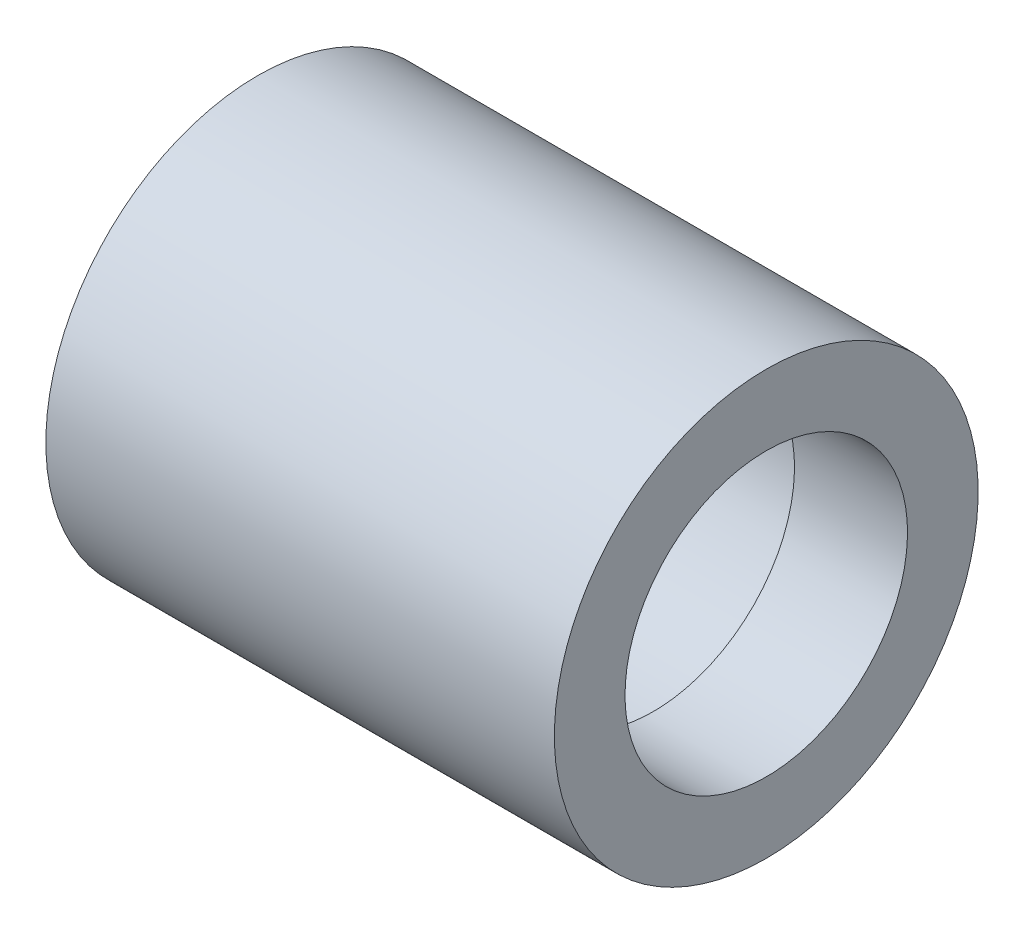
SolidWorks part; units mm, degrees
ref_plane "Front Plane" through (0, 0, 0) normal (0, 0, 1) x (1, 0, 0)
ref_plane "Top Plane" through (0, 0, 0) normal (0, 1, 0) x (1, 0, 0)
ref_plane "Right Plane" through (0, 0, 0) normal (1, 0, 0) x (0, 0, -1)
sketch "Sketch1" plane through (0, 0, 0) normal (0, 0, 1) x (1, 0, 0)
  line L0 (0, 0) -> (0, 26.2355) construction
  line L1 (17, 15) -> (-19, 15)
  line L2 (17, 15) -> (17, 10)
  line L3 (-19, 15) -> (-19, 10)
  line L4 (17, 10) -> (9, 10)
  line L5 (9, 10) -> (9, 12)
  line L6 (9, 12) -> (-9, 12)
  line L7 (-9, 12) -> (-9, 10)
  line L8 (-9, 10) -> (-19, 10)
  line L9 (30.7075, 0) -> (-32.7578, 0) construction
  dimension "D1" = 15
  dimension "D2" = 17
  dimension "D3" = 36
  dimension "D4" = 5
  dimension "D5" = 8
  dimension "D6" = 2
  dimension "D7" = 18
revolve "Revolve1" add sketch "Sketch1" angle 360 about L9
